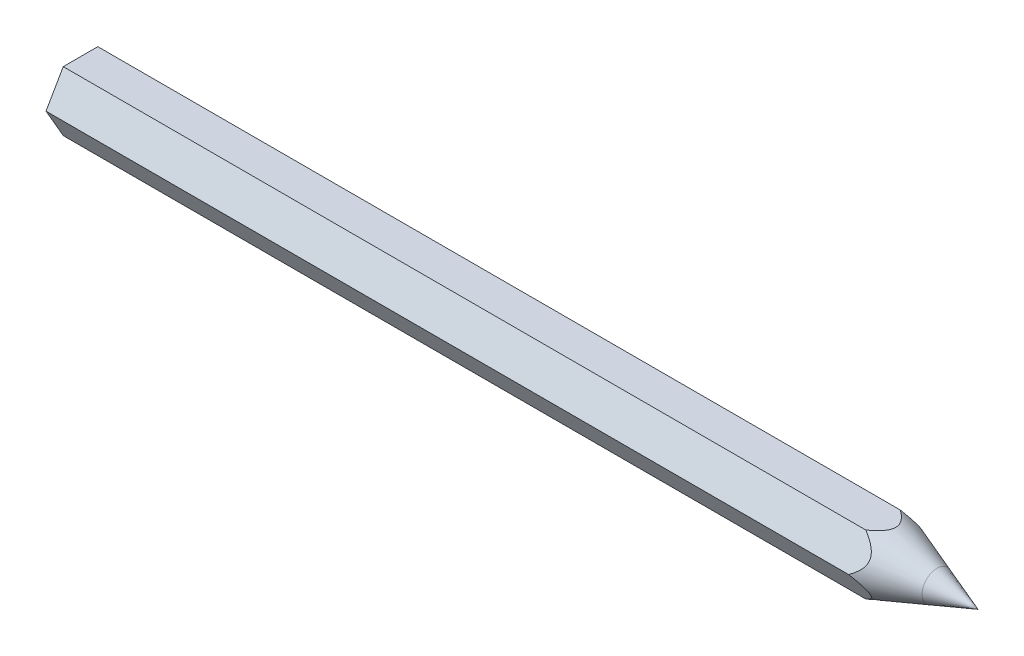
SolidWorks part; units mm, degrees
ref_plane "Front Plane" through (0, 0, 0) normal (1, 0, 0) x (0, 1, 0)
ref_plane "Top Plane" through (0, 0, 0) normal (0, 0, 1) x (0, 1, 0)
ref_plane "Right Plane" through (0, 0, 0) normal (0, 1, 0) x (-1, 0, 0)
sketch "Sketch1" plane through (0, 0, 0) normal (1, 0, 0) x (0, 1, 0)
  line L0 (0, 5.8244) -> (0, 0) construction
  line L1 (5.0025, -2.8824) -> (4.9975, 2.8911)
  line L2 (4.9975, 2.8911) -> (-0.005, 5.7735)
  line L3 (-0.005, 5.7735) -> (-5.0025, 2.8824)
  line L4 (-5.0025, 2.8824) -> (-4.9975, -2.8911)
  line L5 (-4.9975, -2.8911) -> (0.005, -5.7735)
  line L6 (0.005, -5.7735) -> (5.0025, -2.8824)
  circle A0 centre (0, 0) radius 5 construction
  circle A1 centre (0, 0) radius 2.5
  dimension "D1" = 10
  dimension "D2" = 5
extrude "Boss-Extrude1" add sketch "Sketch1" along normal blind 150
sketch "Sketch2" plane through (0, 0, 0) normal (1, 0, 0) x (0, 1, 0)
  circle A0 centre (0, 0) radius 2.5 construction
  circle A1 centre (0, 0) radius 2.5
extrude "Boss-Extrude2" add sketch "Sketch2" along normal up to surface (150 mm away) separate body up to face at (150, 0, 0)
sketch "Sketch3" plane through (0, 0, 0) normal (0, 1, 0) x (-1, 0, 0)
  line L0 (-150, 0.0044) -> (-134.1494, 5.7735)
  line L1 (-150, -2.8824) -> (-150, 2.8911) construction
  line L2 (-150, 5.7735) -> (0, 5.7735) construction
  line L3 (-134.1494, 5.7735) -> (-134.1494, 15.7735)
  line L4 (-134.1494, 15.7735) -> (-160, 15.7735)
  line L5 (-160, 15.7735) -> (-160, 0.0044)
  line L6 (-160, 0.0044) -> (-150, 0.0044)
  dimension "D1" = 20
  dimension "D2" = 10
revolve "Cut-Revolve1" cut sketch "Sketch3" angle 360 about L6
equation "\"B\" = 10"
equation "\"D1@Sketch1\"=\"B\""
equation "\"C\"= 5"
equation "\"D2@Sketch1\"=\"C\""
equation "\"A\" = 150"
equation "\"D1@Boss-Extrude1\"=\"A\""
equation "\"D2@Sketch3\"=\"B\""
